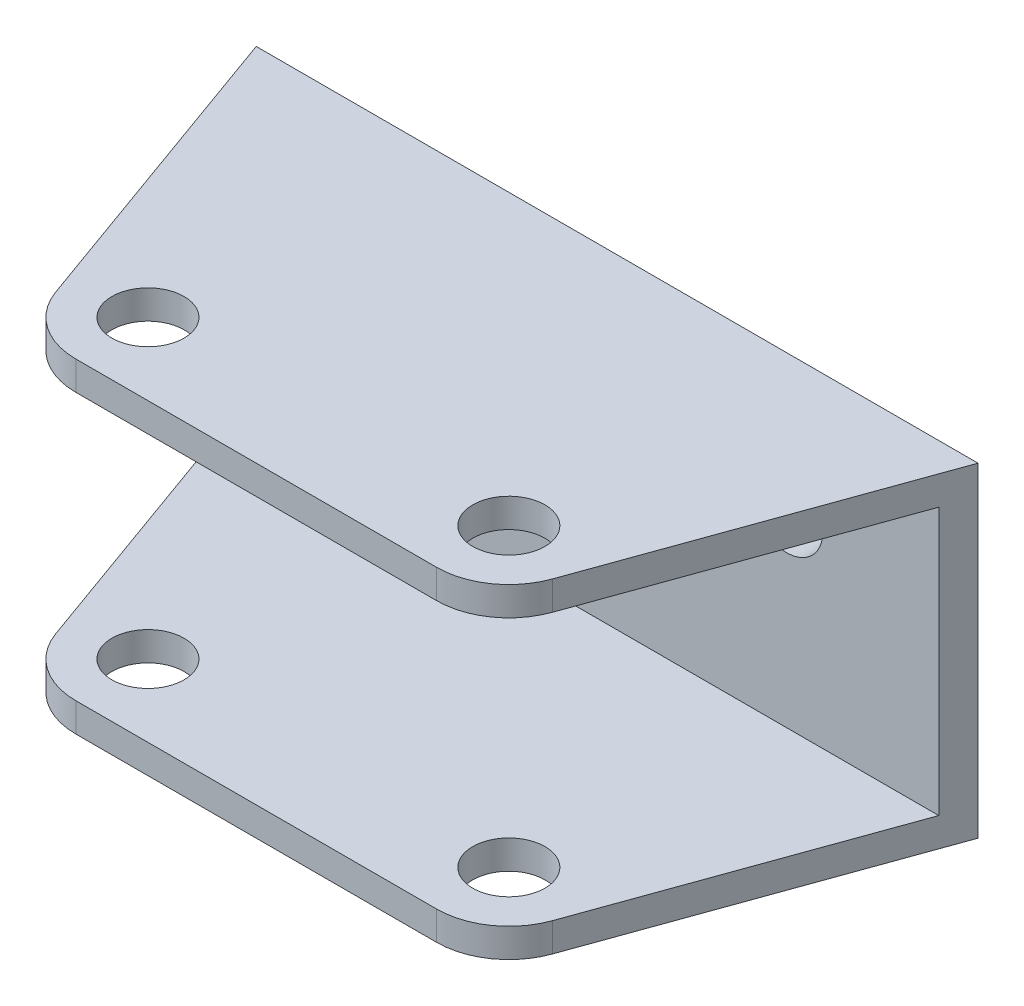
SolidWorks part; units mm, degrees
ref_plane "Front Plane" through (0, 0, 0) normal (0, 0, 1) x (1, 0, 0)
ref_plane "Top Plane" through (0, 0, 0) normal (0, 1, 0) x (1, 0, 0)
ref_plane "Right Plane" through (0, 0, 0) normal (1, 0, 0) x (0, 0, -1)
sketch "Sketch1" plane through (0, 0, 32.9) normal (0, 0, 1) x (1, 0, 0)
  line L0 (-17.5, -114.3) -> (17.5, -114.3) construction
  line L1 (37.241, -99.2999) -> (-37.241, -99.2999) construction
  line L2 (-40, -144.2999) -> (40, -144.2999)
  line L4 (-40, -99.2999) -> (40, -99.2999)
  line L5 (40, -144.2999) -> (40, -99.2999)
  line L6 (-40, -99.2999) -> (-40, -144.2999) construction
  line L7 (-40, -144.2999) -> (-60, -144.2999)
  line L9 (-40, -99.2999) -> (-60, -99.2999)
  line L10 (-60, -144.2999) -> (-60, -99.2999)
  circle A0 centre (17.5, -114.3) radius 5 construction
  circle A1 centre (-17.5, -114.3) radius 5 construction
  circle A2 centre (17.5, -114.3) radius 5
  circle A3 centre (-17.5, -114.3) radius 5
  point P6 (0, -99.2999)
  point P7 (0, -114.3)
  dimension "D1" = 45
  dimension "D2" = 80
  dimension "D3" = 20
extrude "Boss-Extrude1" add sketch "Sketch1" along normal blind 50
sketch "Sketch2" plane through (0, -144.2999, 0) normal (0, -1, 0) x (1, 0, 0)
  line L0 (-35, 72.9) -> (15, 72.9) construction
  line L2 (-60, 82.9) -> (40, 82.9) construction
  line L3 (-60, 32.9) -> (-44.4108, 76.2818)
  line L4 (40, 32.9) -> (24.4108, 76.2818)
  line L5 (-60, 82.9) -> (40, 82.9) construction
  line L6 (-35, 82.9) -> (15, 82.9)
  circle A0 centre (15, 72.9) radius 5
  circle A1 centre (15, 72.9) radius 10
  circle A2 centre (-35, 72.9) radius 5
  circle A3 centre (-35, 72.9) radius 10
  point P0 (-10, 72.9)
  point P2 (-10, 82.9)
  point P23 (-10, 82.9)
  dimension "D1" = 10
  dimension "D3" = 50
  dimension "D2" = 20
extrude "Cut-Extrude1" cut sketch "Sketch2" against normal through all
sketch "Sketch3" plane through (0, 0, 0) normal (1, 0, 0) x (0, 0, -1)
  line L0 (-32.9, -121.7999) -> (-96.9024, -121.7999) construction
  line L1 (-32.9, -99.2999) -> (-32.9, -144.2999) construction
  line L2 (-36.9, -103.2999) -> (-36.9, -140.2999)
  line L3 (-36.9, -140.2999) -> (-102.5865, -140.2999)
  line L4 (-102.5865, -140.2999) -> (-102.5865, -103.2999)
  line L5 (-102.5865, -103.2999) -> (-36.9, -103.2999)
  line L6 (-32.9, -99.2999) -> (-76.2818, -99.2999) construction
  line L7 (-32.9, -144.2999) -> (-76.2818, -144.2999) construction
  dimension "D1" = 4
  dimension "D2" = 4
  dimension "D3" = 4
extrude "Cut-Extrude2" cut sketch "Sketch3" against normal through all both and the other way through all
equation "\"D3@Sketch3\"=\"D1@Sketch3\""
equation "\"D2@Sketch3\"=\"D1@Sketch3\""
